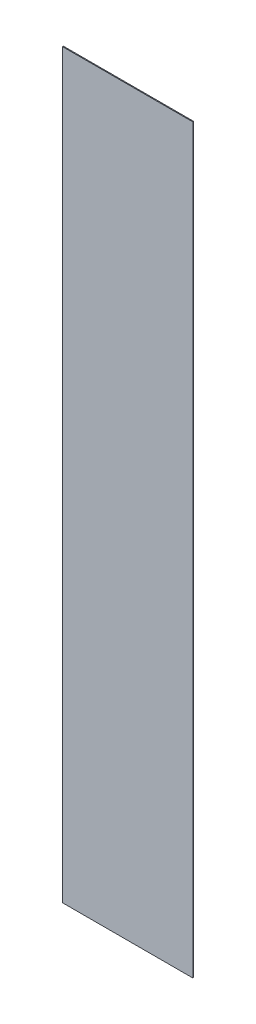
SolidWorks part; units mm, degrees
ref_plane "前基準面" through (0, 0, 0) normal (0, 0, 1) x (1, 0, 0)
ref_plane "上基準面" through (0, 0, 0) normal (0, 1, 0) x (1, 0, 0)
ref_plane "右基準面" through (0, 0, 0) normal (1, 0, 0) x (0, 0, -1)
sketch "草圖1" plane through (0, 0, 0) normal (0, 0, 1) x (1, 0, 0)
  line L1 (0, 0) -> (440, 0)
  line L2 (0, 0) -> (0, 2500)
  line L3 (0, 2500) -> (440, 2500)
  line L4 (440, 0) -> (440, 2500)
  dimension "D1" = 440
  dimension "D2" = 2500
extrude "填料-伸長1" add sketch "草圖1" along normal blind 3
